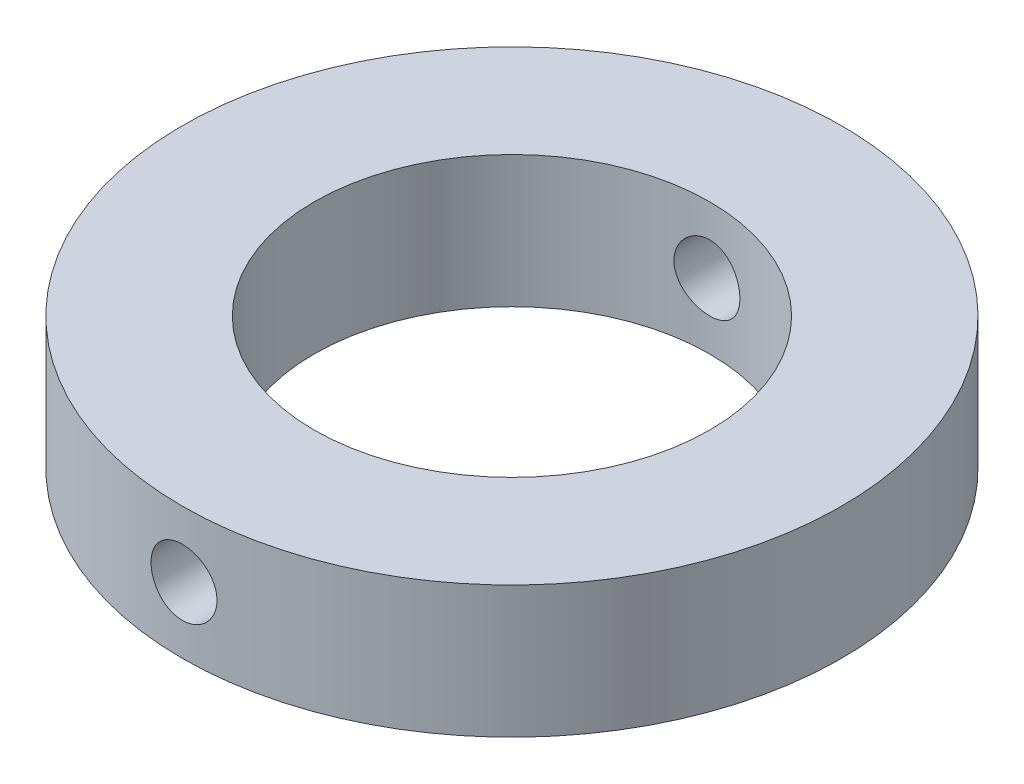
SolidWorks part; units mm, degrees
ref_plane "Front Plane" through (0, 0, 0) normal (0, 0, 1) x (1, 0, 0)
ref_plane "Top Plane" through (0, 0, 0) normal (0, 1, 0) x (1, 0, 0)
ref_plane "Right Plane" through (0, 0, 0) normal (1, 0, 0) x (0, 0, -1)
sketch "Sketch1" plane through (0, 0, 0) normal (0, 1, 0) x (1, 0, 0)
  line L0 (0, 79.7581) -> (0, -68.4849) construction
  line L1 (-107.9412, 0) -> (98.3589, 0) construction
  circle A0 centre (0, 0) radius 25
  circle A1 centre (0, 0) radius 15
extrude "Boss-Extrude1" add sketch "Sketch1" along normal blind 10 contours A0 | A1
sketch "Sketch2" plane through (0, 0, 0) normal (0, 0, 1) x (1, 0, 0)
  circle A0 centre (0, 5) radius 2.5
extrude "Cut-Extrude1" cut sketch "Sketch2" against normal mid plane 100
